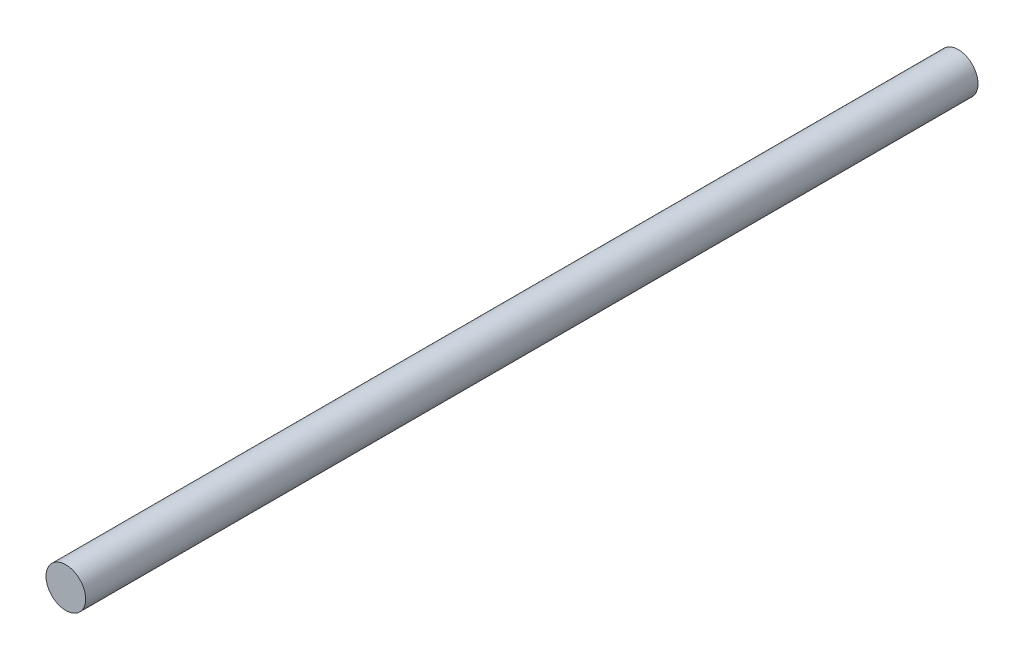
SolidWorks part; units mm, degrees
ref_plane "Front Plane" through (0, 0, 0) normal (0, 0, 1) x (1, 0, 0)
ref_plane "Top Plane" through (0, 0, 0) normal (0, 1, 0) x (1, 0, 0)
ref_plane "Right Plane" through (0, 0, 0) normal (1, 0, 0) x (0, 0, -1)
sketch "Sketch1" plane through (0, 0, 0) normal (0, 0, 1) x (1, 0, 0)
  line L0 (55, 0) -> (-55, 0) construction
  circle A0 centre (-0.2704, 0) radius 2
  dimension "D1" = 4
extrude "Boss-Extrude1" add sketch "Sketch1" along normal blind 90
